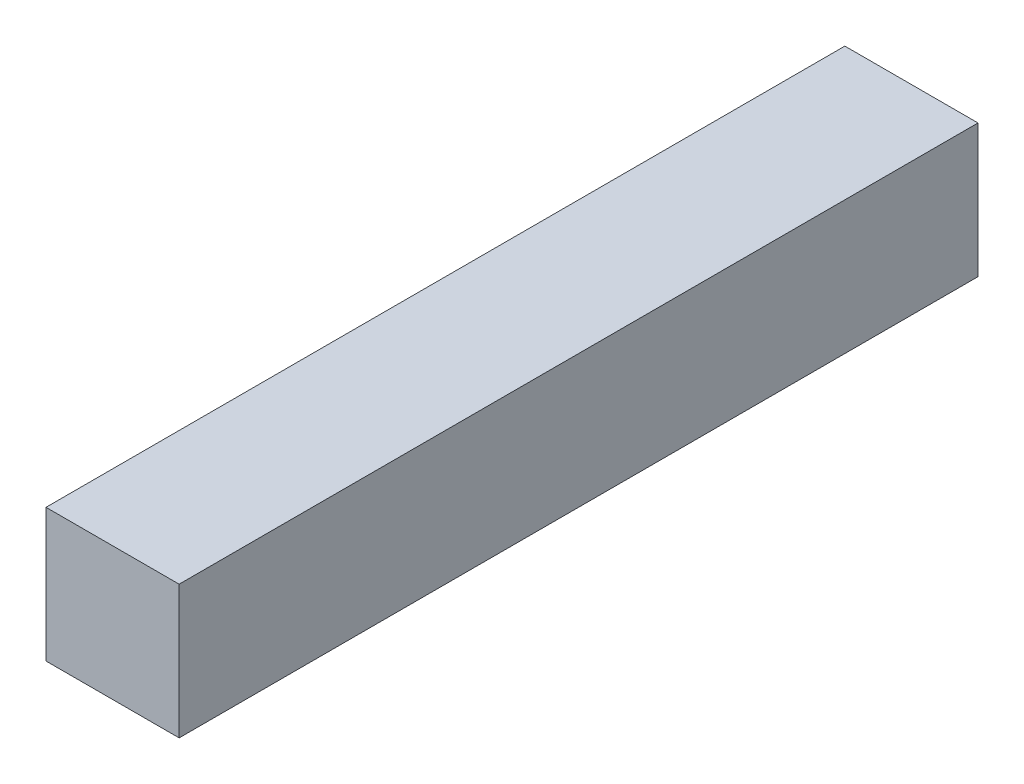
SolidWorks part; units mm, degrees
ref_plane "Front Plane" through (0, 0, 0) normal (0, 0, 1) x (1, 0, 0)
ref_plane "Top Plane" through (0, 0, 0) normal (0, 1, 0) x (1, 0, 0)
ref_plane "Right Plane" through (0, 0, 0) normal (1, 0, 0) x (0, 0, -1)
sketch "Sketch1" plane through (0, 0, 0) normal (0, 0, 1) x (1, 0, 0)
  line L1 (-10, -10) -> (10, -10)
  line L2 (-10, -10) -> (-10, 10)
  line L3 (-10, 10) -> (10, 10)
  line L4 (10, -10) -> (10, 10)
  line L5 (-10, -10) -> (10, 10) construction
  line L6 (-10, 10) -> (10, -10) construction
  point P0 (0, 0)
  dimension "D1" = 20
extrude "Boss-Extrude1" add sketch "Sketch1" along normal blind 120
